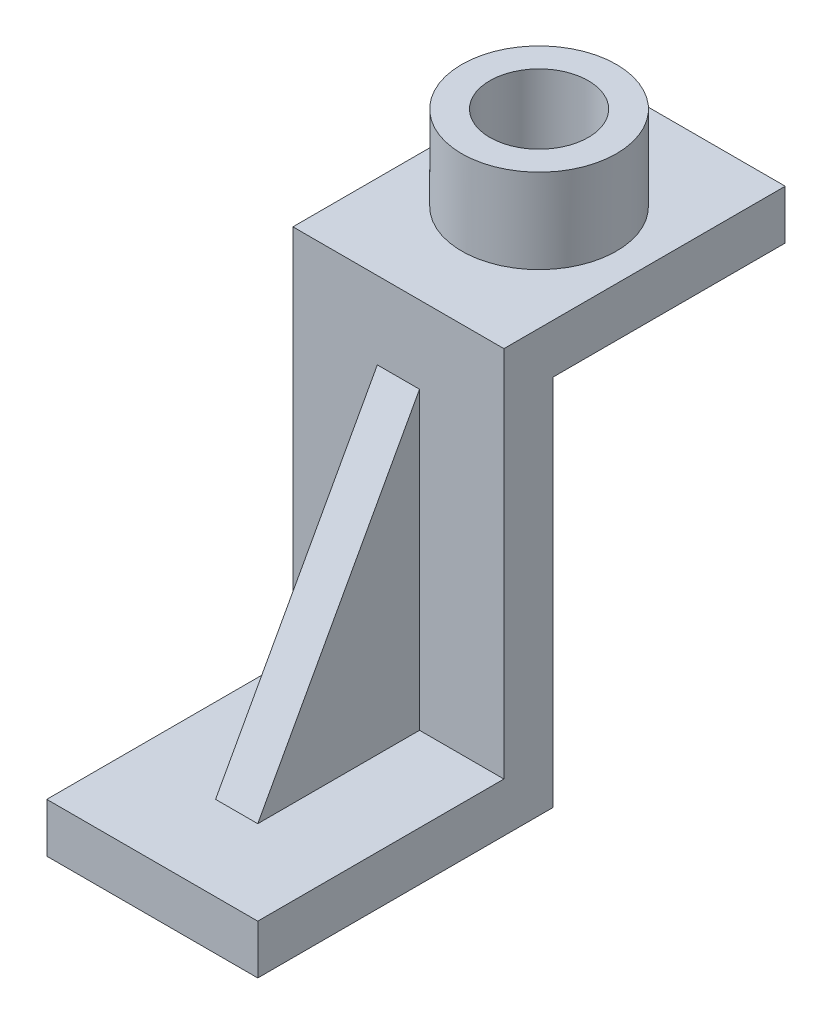
SolidWorks part; units mm, degrees
ref_plane "Front Plane" through (0, 0, 0) normal (0, 0, 1) x (1, 0, 0)
ref_plane "Top Plane" through (0, 0, 0) normal (0, 1, 0) x (1, 0, 0)
ref_plane "Right Plane" through (0, 0, 0) normal (1, 0, 0) x (0, 0, -1)
sketch "Sketch1" plane through (0, 0, 0) normal (0, 0, 1) x (1, 0, 0)
  line L1 (-15, -30) -> (15, -30)
  line L2 (-15, -30) -> (-15, 30)
  line L3 (-15, 30) -> (15, 30)
  line L4 (15, -30) -> (15, 30)
  line L5 (-15, -30) -> (15, 30) construction
  line L6 (-15, 30) -> (15, -30) construction
  point P0 (0, 0)
  dimension "D1" = 30
  dimension "D2" = 60
extrude "Boss-Extrude1" add sketch "Sketch1" along normal blind 7
sketch "Sketch2" plane through (0, 0, 7) normal (0, 0, 1) x (1, 0, 0)
  line L0 (-15, -30) -> (15, -30)
  line L1 (15, -30) -> (15, -23)
  line L2 (15, -30) -> (15, 30) construction
  line L3 (15, -23) -> (-15, -23)
  line L4 (-15, 30) -> (-15, -30) construction
  line L5 (-15, -23) -> (-15, -30)
  dimension "D1" = 7
extrude "Boss-Extrude2" add sketch "Sketch2" along normal blind 35
sketch "Sketch3" plane through (0, 0, 0) normal (1, 0, 0) x (0, 0, -1)
  line L0 (-7, -23) -> (-7, 19)
  line L1 (-7, -23) -> (-7, 30) construction
  line L2 (-7, 19) -> (-30, -23)
  line L3 (-42, -23) -> (-7, -23) construction
  line L4 (-30, -23) -> (-7, -23)
  dimension "D1" = 23
  dimension "D2" = 42
extrude "Boss-Extrude3" add sketch "Sketch3" along normal mid plane 6
sketch "Sketch4" plane through (0, 0, 0) normal (0, 0, -1) x (-1, 0, 0)
  line L0 (15, 30) -> (15, -30) construction
  line L1 (-15, 30) -> (15, 30)
  line L2 (-15, 30) -> (-15, 23)
  line L3 (-15, 23) -> (15, 23)
  line L4 (15, 30) -> (15, 23)
  dimension "D1" = 7
extrude "Boss-Extrude4" add sketch "Sketch4" along normal blind 33
sketch "Sketch5" plane through (0, 30, 0) normal (0, 1, 0) x (1, 0, 0)
  line L0 (15, -7) -> (3, -7) construction
  line L1 (-15, -7) -> (-15, 33) construction
  circle A0 centre (0, 13) radius 11
  circle A1 centre (0, 13) radius 7
  dimension "D1" = 22
  dimension "D2" = 14
  dimension "D3" = 20
  dimension "D4" = 15
extrude "Boss-Extrude5" add sketch "Sketch5" along normal blind 12
sketch "Sketch6" plane through (0, 30, 0) normal (0, 1, 0) x (1, 0, 0)
  circle A0 centre (0, 13) radius 7 construction
  circle A1 centre (0, 13) radius 7
extrude "Cut-Extrude1" cut sketch "Sketch6" against normal blind 12
